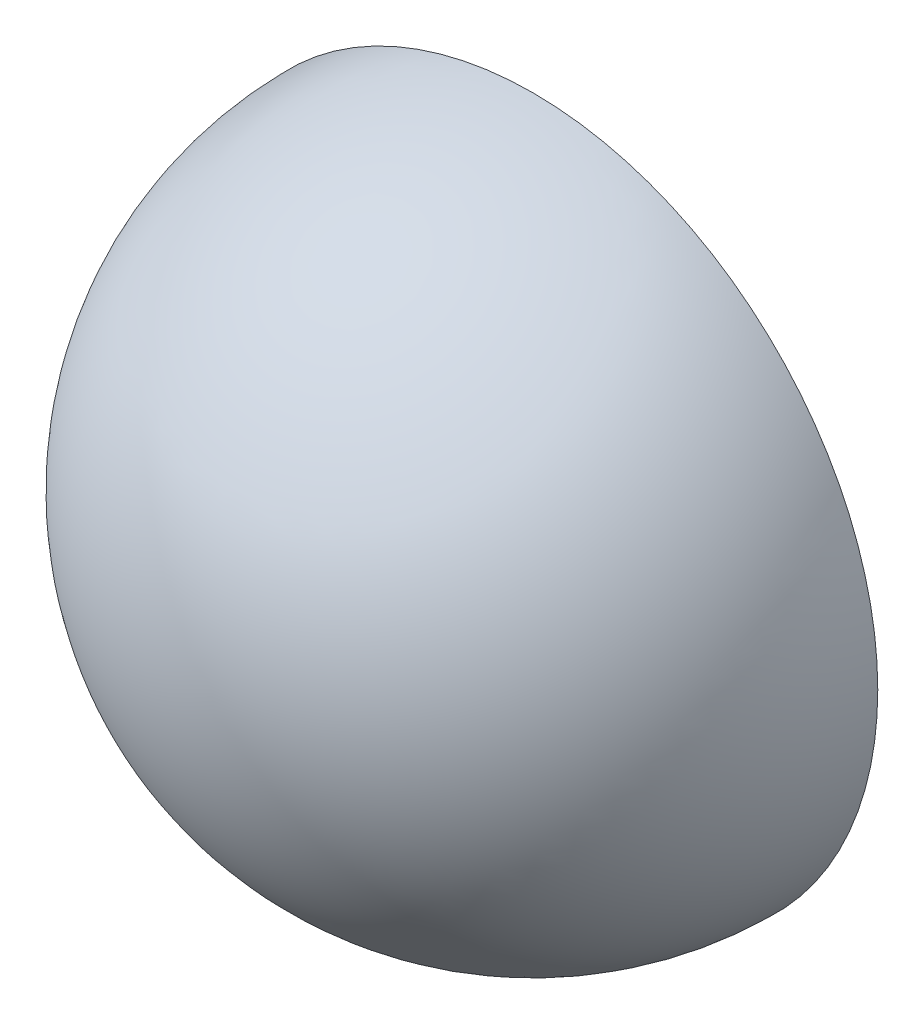
SolidWorks part; units mm, degrees
ref_plane "Front Plane" through (0, 0, 0) normal (0, 0, 1) x (1, 0, 0)
ref_plane "Top Plane" through (0, 0, 0) normal (0, 1, 0) x (1, 0, 0)
ref_plane "Right Plane" through (0, 0, 0) normal (1, 0, 0) x (0, 0, -1)
sketch "Sketch1" plane through (0, 0, 0) normal (1, 0, 0) x (0, 0, -1)
  arc A0 (0, 21.85) -> (-21.85, 0) centre (0, 0) ccw
  dimension "D1" = 21.85
sketch "Sketch3" plane through (0, 0, 0) normal (0, 1, 0) x (1, 0, 0)
  line L0 (0, -45.5726) -> (0, 0) construction
revolve "Revolve-Thin1" add sketch "Sketch1" angle 360 about L0
